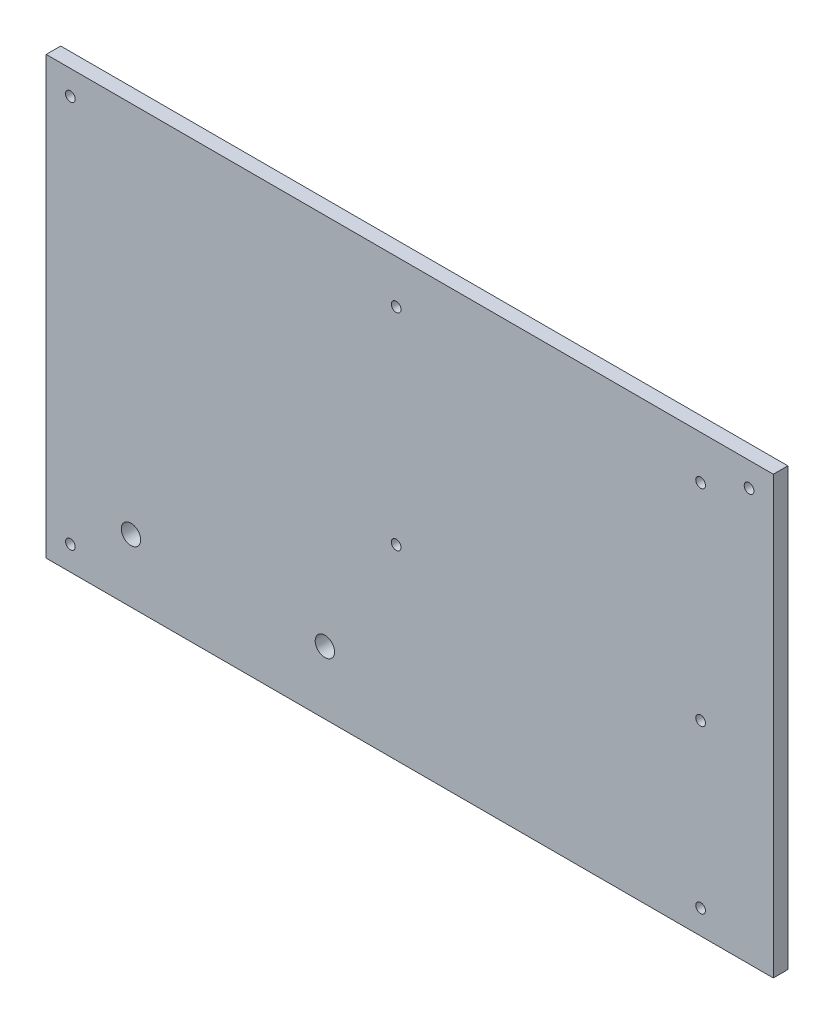
SolidWorks part; units mm, degrees
material "Faia"
ref_plane "Plano frontal" through (0, 0, 0) normal (0, 0, 1) x (1, 0, 0)
ref_plane "Plano superior" through (0, 0, 0) normal (0, 1, 0) x (1, 0, 0)
ref_plane "Plano direito" through (0, 0, 0) normal (1, 0, 0) x (0, 0, -1)
sketch "Esboço1" plane through (0, 0, 0) normal (0, 0, 1) x (1, 0, 0)
  line L0 (150, 0) -> (-150, 0) construction
  line L1 (-150, 90) -> (150, 90)
  line L2 (-150, 90) -> (-150, -90)
  line L3 (-150, -90) -> (150, -90)
  line L4 (150, 90) -> (150, -90)
  line L5 (-150, 90) -> (150, -90) construction
  line L6 (-150, -90) -> (150, 90) construction
  line L7 (140, 80) -> (140, 90) construction
  line L8 (120, -80) -> (120, -90) construction
  line L9 (-115, -64) -> (-35, -64) construction
  circle A0 centre (120, -80) radius 2
  circle A1 centre (140, 80) radius 2
  circle A2 centre (-140, 80) radius 2
  circle A3 centre (-140, -80) radius 2
  circle A4 centre (-115, -64) radius 4
  circle A5 centre (-35, -64) radius 4
  point P0 (0, 0)
  point P21 (5, 0)
  point P23 (-75, -64)
  dimension "D5" = 30
  dimension "D8" = 80
  dimension "D10" = 75
  dimension "D3" = 4
  dimension "D11" = 8
  dimension "D1" = 300
  dimension "D2" = 180
  dimension "D4" = 10
  dimension "D7" = 10
  dimension "D9" = 26
  dimension "D6" = 10
extrude "Ressalto-extrusão1" add sketch "Esboço1" along normal blind 6
sketch "Esboço2" plane through (0, 0, 6) normal (0, 0, 1) x (1, 0, 0)
  line L0 (-150, 90) -> (150, 90) construction
  line L1 (150, 90) -> (150, -90) construction
  circle A0 centre (120, 72) radius 2
  circle A1 centre (-5.6, 72) radius 2
  circle A2 centre (-5.6, -13) radius 2
  circle A3 centre (120, -13) radius 2
  dimension "D2" = 4
  dimension "D1" = 125.6
  dimension "D3" = 85
  dimension "D4" = 18
  dimension "D5" = 30
extrude "Corte-extrusão1" cut sketch "Esboço2" against normal blind 10
